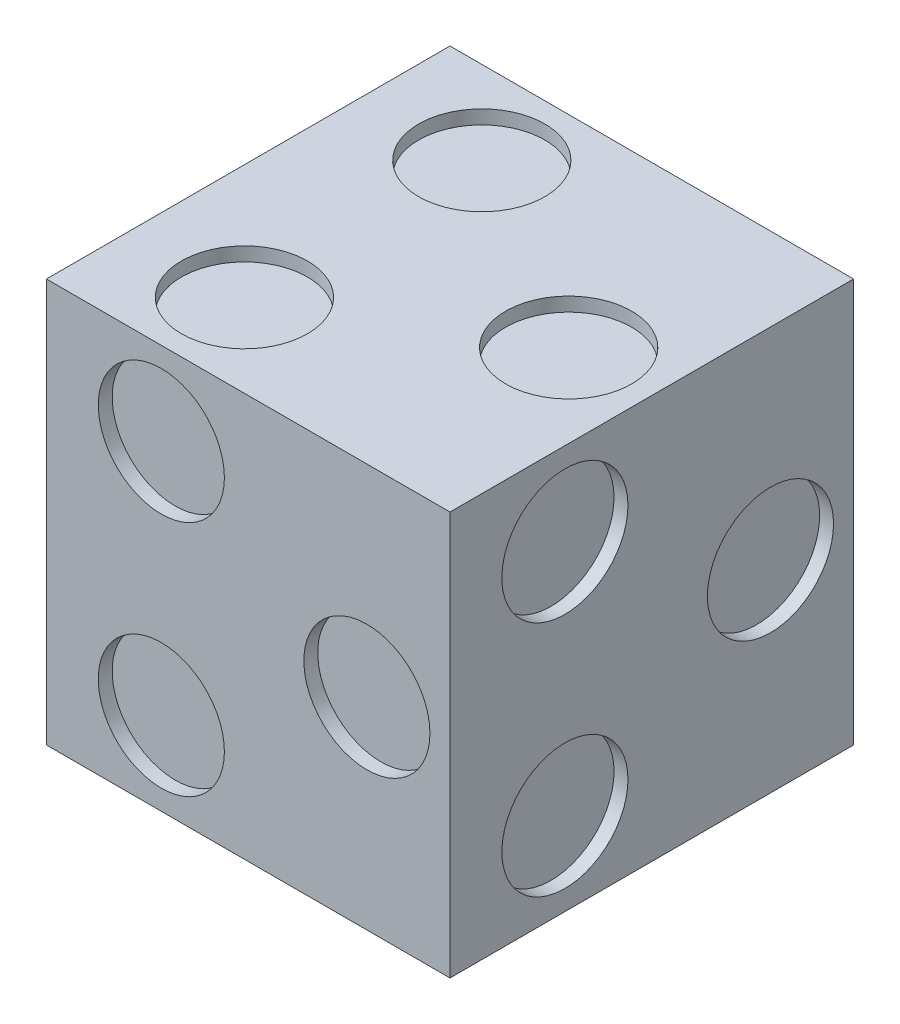
SolidWorks part; units mm, degrees
material "Custom Plastic"
ref_plane "Front Plane" through (0, 0, 0) normal (0, 0, 1) x (1, 0, 0)
ref_plane "Top Plane" through (0, 0, 0) normal (0, 1, 0) x (1, 0, 0)
ref_plane "Right Plane" through (0, 0, 0) normal (1, 0, 0) x (0, 0, -1)
sketch "Sketch1" plane through (0, 0, 0) normal (0, 1, 0) x (1, 0, 0)
  line L1 (0, 0) -> (101.6, 0)
  line L2 (0, 0) -> (0, 101.6)
  line L3 (0, 101.6) -> (101.6, 101.6)
  line L4 (101.6, 0) -> (101.6, 101.6)
  point P4 (0, 0)
  point P6 (0, 0)
  point P7 (0, 0)
  point P8 (0, 0)
extrude "Boss-Extrude2" add sketch "Sketch1" along normal blind 101.6
sketch "Sketch3" plane through (0, 101.6, 0) normal (0, 1, 0) x (1, 0, 0)
  line L0 (28.9279, 20.9221) -> (80.6779, 50.8) construction
  line L1 (80.6779, 50.8) -> (28.9279, 80.6779) construction
  line L2 (28.9279, 80.6779) -> (28.9279, 20.9221) construction
  line L4 (28.9279, 80.6779) -> (28.9279, 101.6) construction
  line L8 (101.6, 101.6) -> (0, 101.6) construction
  line L9 (28.9279, 20.9221) -> (28.9279, 0) construction
  line L10 (0, 0) -> (101.6, 0) construction
  line L11 (80.6779, 50.8) -> (101.6, 50.8) construction
  line L12 (101.6, 0) -> (101.6, 101.6) construction
  circle A0 centre (46.1779, 50.8) radius 34.5 construction
  circle A1 centre (28.9279, 20.9221) radius 15.875
  circle A2 centre (28.9279, 80.6779) radius 15.875
  circle A3 centre (80.6779, 50.8) radius 15.875
  point P17 (0, 0)
  point P18 (0, 0)
  point P19 (0, 0)
  dimension "D1" = 31.75
  dimension "D2" = 69
extrude "Cut-Extrude1" cut sketch "Sketch3" against normal blind 3.5
sketch "Sketch4" plane through (0, 0, 0) normal (-1, 0, 0) x (0, 0, 1)
  line L0 (-72.6721, 20.9221) -> (-20.9221, 50.8) construction
  line L1 (-20.9221, 50.8) -> (-72.6721, 80.6779) construction
  line L2 (-72.6721, 80.6779) -> (-72.6721, 20.9221) construction
  line L3 (0, 101.6) -> (0, 0) construction
  line L4 (-72.6721, 80.6779) -> (-72.6721, 101.6) construction
  line L5 (-101.6, 101.6) -> (0, 101.6) construction
  line L6 (-101.6, 0) -> (0, 0) construction
  line L9 (-72.6721, 20.9221) -> (-72.6721, 0) construction
  line L11 (-20.9221, 50.8) -> (0, 50.8) construction
  circle A0 centre (-55.4221, 50.8) radius 34.5 construction
  circle A1 centre (-72.6721, 20.9221) radius 15.875
  circle A2 centre (-72.6721, 80.6779) radius 15.875
  circle A3 centre (-20.9221, 50.8) radius 15.875
  point P11 (0, 0)
  point P14 (0, 0)
  point P15 (0, 0)
  point P17 (-137.3109, 13.7285)
  point P18 (-137.3109, 13.7285)
  point P19 (-137.3109, 13.7285)
  point P21 (0, 0)
  dimension "D1" = 31.75
  dimension "D2" = 69
sketch "Sketch5" plane through (0, 0, -101.6) normal (0, 0, -1) x (-1, 0, 0)
  line L0 (-72.6721, 20.9221) -> (-20.9221, 50.8) construction
  line L1 (-20.9221, 50.8) -> (-72.6721, 80.6779) construction
  line L2 (-72.6721, 80.6779) -> (-72.6721, 20.9221) construction
  line L3 (-101.6, 101.6) -> (0, 101.6) construction
  line L4 (-72.6721, 80.6779) -> (-72.6721, 101.6) construction
  line L5 (-101.6, 0) -> (0, 0) construction
  line L6 (0, 101.6) -> (0, 0) construction
  line L9 (-72.6721, 20.9221) -> (-72.6721, 0) construction
  line L11 (-20.9221, 50.8) -> (0, 50.8) construction
  circle A0 centre (-55.4221, 50.8) radius 34.5 construction
  circle A1 centre (-72.6721, 20.9221) radius 15.875
  circle A2 centre (-72.6721, 80.6779) radius 15.875
  circle A3 centre (-20.9221, 50.8) radius 15.875
  point P11 (0, 0)
  point P14 (0, 0)
  point P17 (-112.8103, -3.1048)
  point P18 (-112.8103, -3.1048)
  point P19 (-112.8103, -3.1048)
  point P20 (0, 0)
  dimension "D1" = 31.75
  dimension "D2" = 69
sketch "Sketch6" plane through (101.6, 0, 0) normal (1, 0, 0) x (0, 0, -1)
  line L0 (28.9279, 20.9221) -> (80.6779, 50.8) construction
  line L1 (80.6779, 50.8) -> (28.9279, 80.6779) construction
  line L2 (28.9279, 80.6779) -> (28.9279, 20.9221) construction
  line L3 (0, 101.6) -> (101.6, 101.6) construction
  line L4 (28.9279, 80.6779) -> (28.9279, 101.6) construction
  line L5 (101.6, 101.6) -> (101.6, 0) construction
  line L6 (0, 0) -> (101.6, 0) construction
  line L9 (28.9279, 20.9221) -> (28.9279, 0) construction
  line L11 (80.6779, 50.8) -> (101.6, 50.8) construction
  circle A0 centre (46.1779, 50.8) radius 34.5 construction
  circle A1 centre (28.9279, 20.9221) radius 15.875
  circle A2 centre (28.9279, 80.6779) radius 15.875
  circle A3 centre (80.6779, 50.8) radius 15.875
  point P11 (0, 0)
  point P14 (0, 0)
  point P15 (0, 0)
  point P17 (-20.5356, -34.0061)
  point P18 (-20.5356, -34.0061)
  point P19 (-20.5356, -34.0061)
  point P21 (0, 0)
  dimension "D1" = 31.75
  dimension "D2" = 69
sketch "Sketch7" plane through (0, 0, 0) normal (0, 0, 1) x (1, 0, 0)
  line L0 (28.9279, 20.9221) -> (80.6779, 50.8) construction
  line L1 (80.6779, 50.8) -> (28.9279, 80.6779) construction
  line L2 (28.9279, 80.6779) -> (28.9279, 20.9221) construction
  line L3 (101.6, 101.6) -> (101.6, 0) construction
  line L4 (28.9279, 80.6779) -> (28.9279, 101.6) construction
  line L5 (0, 101.6) -> (101.6, 101.6) construction
  line L6 (0, 0) -> (101.6, 0) construction
  line L9 (28.9279, 20.9221) -> (28.9279, 0) construction
  line L11 (80.6779, 50.8) -> (101.6, 50.8) construction
  circle A0 centre (46.1779, 50.8) radius 34.5 construction
  circle A1 centre (28.9279, 20.9221) radius 15.875
  circle A2 centre (28.9279, 80.6779) radius 15.875
  circle A3 centre (80.6779, 50.8) radius 15.875
  point P11 (0, 0)
  point P14 (0, 0)
  point P17 (-15.1194, 1.676)
  point P18 (-15.1194, 1.676)
  point P19 (-15.1194, 1.676)
  point P20 (0, 0)
  dimension "D1" = 31.75
  dimension "D2" = 69
sketch "Sketch8" plane through (0, 0, 0) normal (0, -1, 0) x (-1, 0, 0)
  line L0 (-72.6721, 20.9221) -> (-20.9221, 50.8) construction
  line L1 (-20.9221, 50.8) -> (-72.6721, 80.6779) construction
  line L2 (-72.6721, 80.6779) -> (-72.6721, 20.9221) construction
  line L3 (0, 101.6) -> (0, 0) construction
  line L4 (-72.6721, 80.6779) -> (-72.6721, 101.6) construction
  line L5 (0, 0) -> (-101.6, 0) construction
  line L6 (-101.6, 101.6) -> (0, 101.6) construction
  line L9 (-72.6721, 20.9221) -> (-72.6721, 0) construction
  line L11 (-20.9221, 50.8) -> (0, 50.8) construction
  circle A0 centre (-55.4221, 50.8) radius 34.5 construction
  circle A1 centre (-72.6721, 20.9221) radius 15.875
  circle A2 centre (-72.6721, 80.6779) radius 15.875
  circle A3 centre (-20.9221, 50.8) radius 15.875
  point P11 (0, 0)
  point P14 (0, 0)
  point P17 (-101.2893, 8.6028)
  point P18 (-101.2893, 8.6028)
  point P19 (-101.2893, 8.6028)
  point P20 (0, 0)
  dimension "D1" = 31.75
  dimension "D2" = 69
extrude "Cut-Extrude2" cut sketch "Sketch4" against normal blind 3.5
extrude "Cut-Extrude3" cut sketch "Sketch5" against normal blind 3.5
extrude "Cut-Extrude4" cut sketch "Sketch6" against normal blind 3.5
extrude "Cut-Extrude5" cut sketch "Sketch7" against normal blind 3.5
extrude "Cut-Extrude6" cut sketch "Sketch8" against normal blind 3.5
